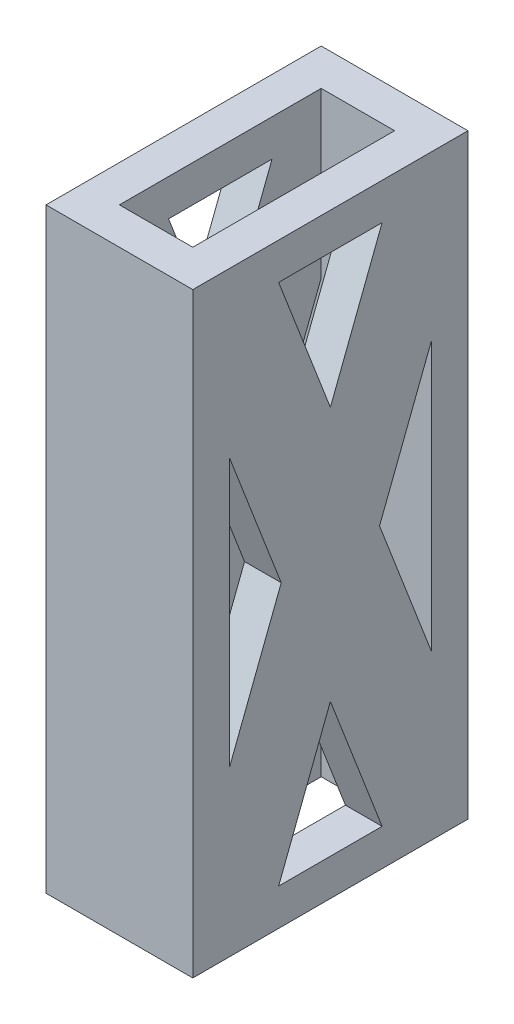
SolidWorks part; units mm, degrees
ref_plane "前视基准面" through (0, 0, 0) normal (0, 0, 1) x (1, 0, 0)
ref_plane "上视基准面" through (0, 0, 0) normal (0, 1, 0) x (1, 0, 0)
ref_plane "右视基准面" through (0, 0, 0) normal (1, 0, 0) x (0, 0, -1)
sketch "Sketch1" plane through (0, 0, 0) normal (0, 1, 0) x (1, 0, 0)
  line L0 (2, -2) -> (2, -13)
  line L1 (0, 0) -> (8, 0)
  line L2 (0, 0) -> (0, -15)
  line L3 (0, -15) -> (8, -15)
  line L4 (8, 0) -> (8, -15)
  line L5 (2, -13) -> (6, -13)
  line L6 (6, -2) -> (6, -13)
  line L7 (2, -2) -> (6, -2)
  dimension "D1" = 8
  dimension "D2" = 15
  dimension "D3" = 2
extrude "Boss-Extrude1" add sketch "Sketch1" along normal blind 32.5
sketch "Sketch2" plane through (8, 0, 0) normal (1, 0, 0) x (0, 0, -1)
  line L0 (-13, 30.5) -> (-2, 2) construction
  line L1 (-2, 30.5) -> (-13, 2) construction
  line L2 (-15, 32.5) -> (0, 32.5)
  line L3 (0, 32.5) -> (0, 0)
  line L4 (0, 0) -> (-15, 0)
  line L5 (-15, 0) -> (-15, 32.5) construction
  line L6 (-13, 8.943) -> (-13, 23.557)
  line L7 (-10.3203, 30.5) -> (-4.6797, 30.5)
  line L8 (-2, 23.557) -> (-2, 8.943)
  line L9 (-4.6797, 2) -> (-10.3203, 2)
  line L10 (-10.1797, 16.25) -> (-13, 8.943)
  line L11 (-4.6797, 30.5) -> (-7.5, 23.193)
  line L12 (-10.3203, 30.5) -> (-7.5, 23.193)
  line L13 (-2, 23.557) -> (-4.8203, 16.25)
  line L14 (-13, 23.557) -> (-10.1797, 16.25)
  line L15 (-10.6677, 31.4002) -> (0.3323, 2.9002) construction
  line L16 (-4.3323, 31.4002) -> (-15.3323, 2.9002) construction
  line L17 (0.3323, 29.5998) -> (-10.6677, 1.0998) construction
  line L18 (-13, 30.5) -> (-2, 30.5) construction
  line L19 (-13, 2) -> (-13, 30.5) construction
  line L20 (-4.8203, 16.25) -> (-2, 8.943)
  line L21 (-7.5, 9.307) -> (-4.6797, 2)
  line L22 (-2, 30.5) -> (-2, 2) construction
  line L23 (-7.5, 9.307) -> (-10.3203, 2)
  line L25 (-2, 2) -> (-13, 2) construction
  point P12 (-15.3323, 29.5998)
  point P13 (-4.3323, 1.0998)
  dimension "D4" = 2.5
  dimension "D1" = 2
  dimension "D2" = 2.5
  dimension "D3" = 2.5
extrude "Cut-Extrude1" cut sketch "Sketch2" against normal through all contours L7 L12 L11 | L14 L6 L10 | L13 L20 L8 | L21 L23 L9
